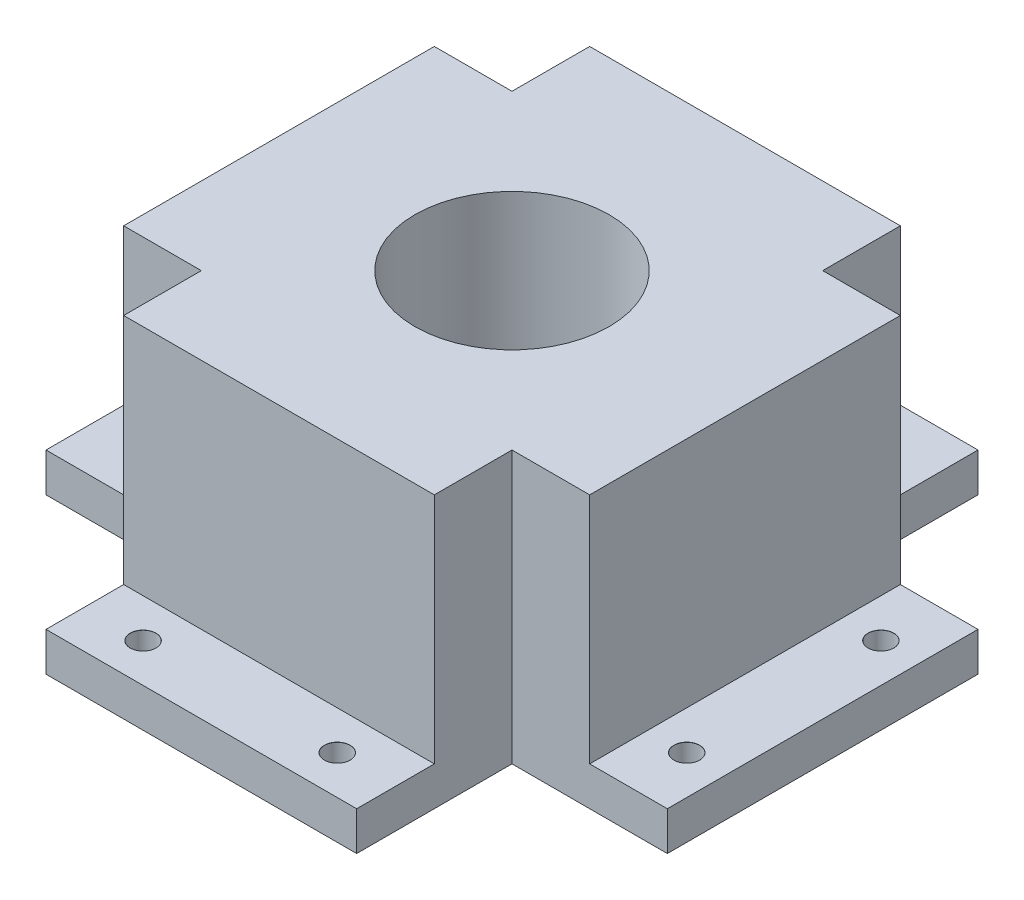
SolidWorks part; units mm, degrees
ref_plane "Front Plane" through (0, 0, 0) normal (0, 0, 1) x (1, 0, 0)
ref_plane "Top Plane" through (0, 0, 0) normal (0, 1, 0) x (1, 0, 0)
ref_plane "Right Plane" through (0, 0, 0) normal (1, 0, 0) x (0, 0, -1)
sketch "Sketch1" plane through (0, 0, 0) normal (0, 1, 0) x (1, 0, 0)
  line L1 (-80, 80) -> (80, 80)
  line L2 (-80, 80) -> (-80, -80)
  line L3 (-80, -80) -> (80, -80)
  line L4 (80, 80) -> (80, -80)
  line L5 (-80, 80) -> (80, -80) construction
  line L6 (-80, -80) -> (80, 80) construction
  point P0 (0, 0)
  dimension "D1" = 160
  dimension "D2" = 160
extrude "Boss-Extrude1" add sketch "Sketch1" along normal blind 70
sketch "Sketch2" plane through (0, 70, 0) normal (0, 1, 0) x (1, 0, 0)
  line L1 (-80, 80) -> (-40, 80)
  line L2 (-80, 80) -> (-80, 40)
  line L3 (-80, 40) -> (-40, 40)
  line L4 (-40, 80) -> (-40, 40)
  line L5 (80, 80) -> (40, 80)
  line L6 (80, 80) -> (80, 40)
  line L7 (80, 40) -> (40, 40)
  line L8 (40, 80) -> (40, 40)
  line L9 (-80, -80) -> (-40, -80)
  line L10 (-80, -80) -> (-80, -40)
  line L11 (-80, -40) -> (-40, -40)
  line L12 (-40, -80) -> (-40, -40)
  line L13 (80, -80) -> (40, -80)
  line L14 (80, -80) -> (80, -40)
  line L15 (80, -40) -> (40, -40)
  line L16 (40, -80) -> (40, -40)
  dimension "D1" = 80
  dimension "D2" = 80
  dimension "D3" = 80
  dimension "D4" = 80
extrude "Cut-Extrude1" cut sketch "Sketch2" against normal through all
sketch "Sketch3" plane through (0, 70, 0) normal (0, 1, 0) x (1, 0, 0)
  line L4 (-40, 40) -> (-40, 80)
  line L5 (-40, 80) -> (40, 80)
  line L6 (40, 80) -> (40, 40)
  line L7 (40, 40) -> (80, 40)
  line L8 (80, 40) -> (80, -40)
  line L9 (80, -40) -> (40, -40)
  line L10 (40, -80) -> (-40, -80)
  line L11 (-40, -80) -> (-40, -40)
  line L12 (-80, -40) -> (-80, 40)
  line L13 (-80, 40) -> (-40, 40)
  line L14 (-80, -40) -> (-40, -40)
  line L15 (-80, 40) -> (-40, 40)
  line L16 (40, -40) -> (40, -80)
  line L17 (-60, 40) -> (-60, -40)
  line L18 (60, 40) -> (60, -40)
  line L19 (-40, -60) -> (40, -60)
  line L20 (-40, 60) -> (40, 60)
  dimension "D1" = 20
  dimension "D2" = 20
  dimension "D3" = 20
  dimension "D4" = 20
extrude "Cut-Extrude2" cut sketch "Sketch3" against normal offset from surface (60 mm away) 10
sketch "Sketch4" plane through (0, 70, 0) normal (0, 1, 0) x (1, 0, 0)
  circle A0 centre (0, 0) radius 25
  dimension "D1" = 50
extrude "Cut-Extrude3" cut sketch "Sketch4" against normal up to next
hole_wizard "M6 Clearance Hole1" positions "Sketch5" profile "Sketch6" hole size "M6" standard "ANSI Metric" end condition through all
sketch "Sketch5" plane through (0, 10, 0) normal (0, 1, 0) x (1, 0, 0)
  line L0 (-70, 25) -> (-70, -25) construction
  line L2 (-25, -70) -> (25, -70) construction
  line L4 (70, -25) -> (70, 25) construction
  line L6 (25, 70) -> (-25, 70) construction
  line L8 (-80, -40) -> (-80, 40) construction
  line L9 (-40, 80) -> (40, 80) construction
  line L10 (80, 40) -> (80, -40) construction
  line L11 (40, -80) -> (-40, -80) construction
  point P0 (-70, 25)
  point P2 (-70, -25)
  point P4 (-25, 70)
  point P6 (25, 70)
  point P8 (70, 25)
  point P10 (70, -25)
  point P12 (25, -70)
  point P14 (-25, -70)
  point P31 (-70, 0)
  point P33 (70, 0)
  point P34 (0, 70)
  point P35 (0, -70)
  dimension "D1" = 50
  dimension "D2" = 10
  dimension "D3" = 10
  dimension "D4" = 10
  dimension "D5" = 10
sketch "Sketch6" plane through (-70, 10, -25) normal (1, 0, 0) x (0, 0, 1)
  line L0 (0, 0) -> (0, 10)
  line L1 (0, 10) -> (3.3, 10)
  line L2 (3.3, 10) -> (3.3, 0.021)
  line L3 (3.3, 0.021) -> (3.325, 0)
  line L5 (3.325, 0) -> (0, 0)
  line L6 (-3.3, 0.021) -> (-3.325, 0) construction
  line L11 (0, -6.35) -> (0, 107.95) construction
  dimension "Thru Hole Dia." = 6.6
  dimension "Thru Hole Depth" = 10
  dimension "Near C'Sink Dia." = 6.65
  dimension "Near C'Sink Angle" = 100
